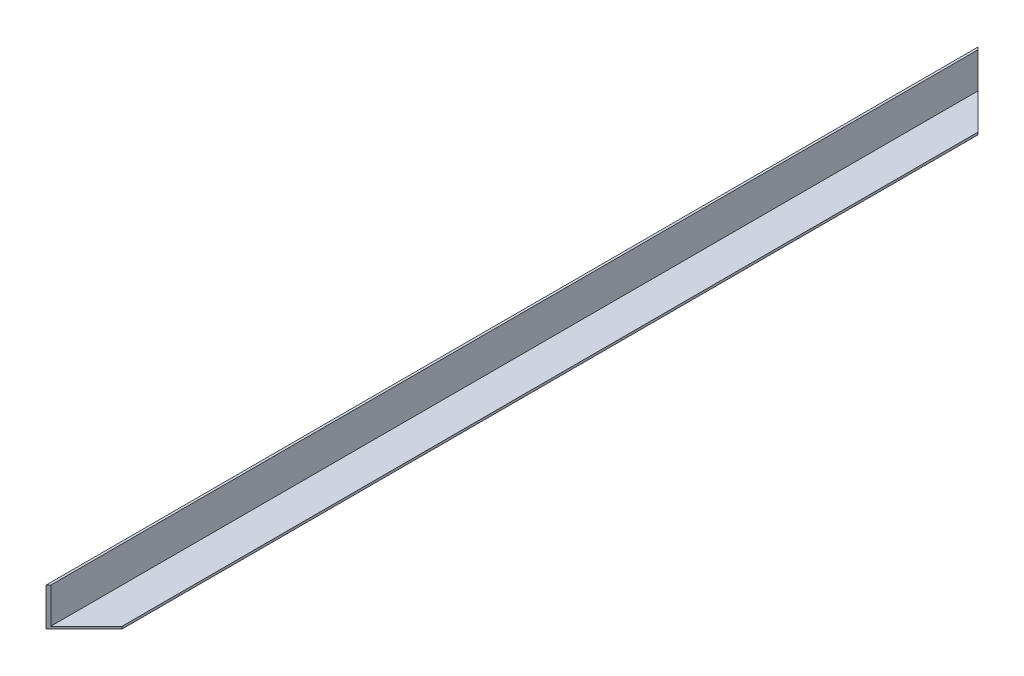
SolidWorks part; units mm, degrees
ref_plane "Front Plane" through (0, 0, 0) normal (0, 0, 1) x (1, 0, 0)
ref_plane "Top Plane" through (0, 0, 0) normal (0, 1, 0) x (1, 0, 0)
ref_plane "Right Plane" through (0, 0, 0) normal (1, 0, 0) x (0, 0, -1)
sketch "Sketch1" plane through (0, 0, 0) normal (0, 0, 1) x (1, 0, 0)
  line L0 (0, 0) -> (0, 15)
  line L1 (0, 0) -> (15, 0)
extrude "Extrude-Thin1" add sketch "Sketch1" along normal blind 392 thin thin type one direction wall 1
sketch "Sketch2" plane through (0, -1, 0) normal (0, -1, 0) x (1, 0, 0)
  line L0 (-1, 392) -> (15, 376)
  line L1 (15, 392) -> (15, 0) construction
  line L2 (15, 376) -> (15, 392)
  line L3 (15, 392) -> (-1, 392)
  line L4 (15, 196) -> (138.2172, 196) construction
  line L5 (15, 16) -> (15, 0)
  line L6 (15, 0) -> (-1, 0)
  line L7 (-1, 0) -> (15, 16)
extrude "Cut-Extrude1" cut sketch "Sketch2" against normal through all
